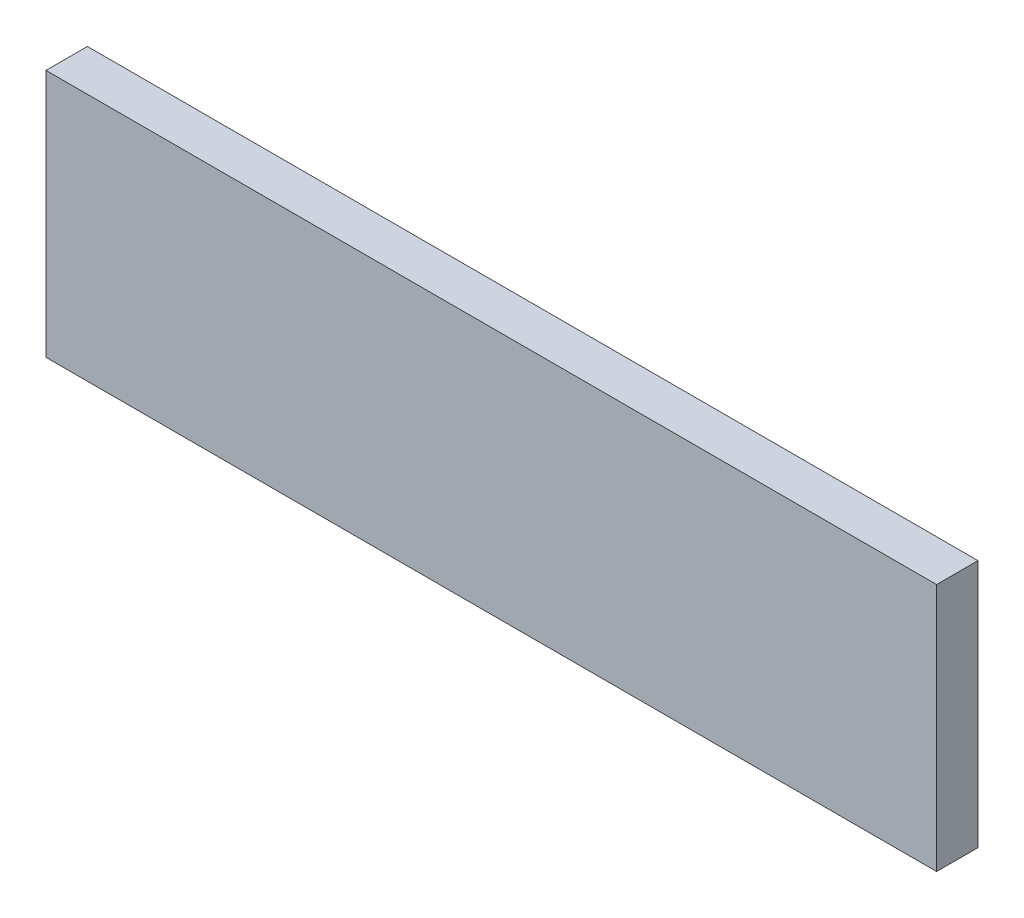
SolidWorks part; units mm, degrees
ref_plane "Front Plane" through (0, 0, 0) normal (0, 0, 1) x (1, 0, 0)
ref_plane "Top Plane" through (0, 0, 0) normal (0, 1, 0) x (1, 0, 0)
ref_plane "Right Plane" through (0, 0, 0) normal (1, 0, 0) x (0, 0, -1)
sketch "Sketch1" plane through (0, 0, 0) normal (1, 0, 0) x (0, 0, -1)
  line L1 (0, 0) -> (50.8, 0)
  line L2 (0, 0) -> (0, 304.8)
  line L3 (0, 304.8) -> (50.8, 304.8)
  line L4 (50.8, 0) -> (50.8, 304.8)
extrude "Boss-Extrude1" add sketch "Sketch1" along normal blind 1092.2
